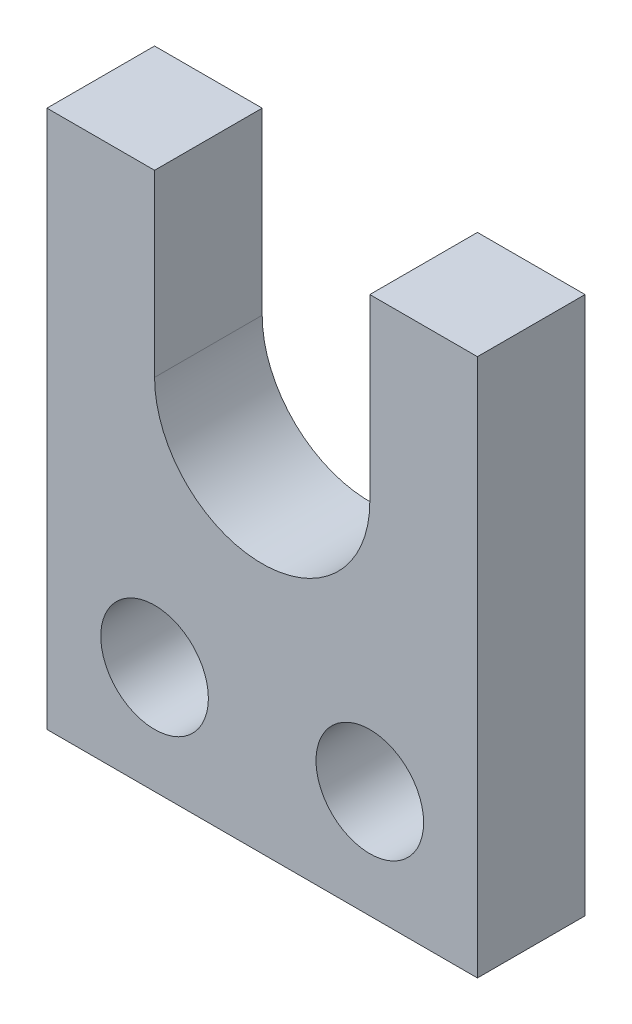
SolidWorks part; units mm, degrees
ref_plane "Front Plane" through (0, 0, 0) normal (0, 0, 1) x (1, 0, 0)
ref_plane "Top Plane" through (0, 0, 0) normal (0, 1, 0) x (1, 0, 0)
ref_plane "Right Plane" through (0, 0, 0) normal (1, 0, 0) x (0, 0, -1)
sketch "Sketch1" plane through (0, 0, 0) normal (0, 0, 1) x (1, 0, 0)
  line L1 (-6, 7.5) -> (6, 7.5)
  line L2 (-6, 7.5) -> (-6, -7.5)
  line L3 (-6, -7.5) -> (6, -7.5)
  line L4 (6, 7.5) -> (6, -7.5)
  line L5 (-6, 7.5) -> (6, -7.5) construction
  line L6 (-6, -7.5) -> (6, 7.5) construction
  circle A0 centre (-3, -4.5) radius 1.5
  circle A1 centre (3, -4.5) radius 1.5
  circle A2 centre (0, 16.5) radius 3 construction
  point P0 (0, 0)
  dimension "D3" = 3
  dimension "D4" = 3
  dimension "D5" = 6
  dimension "D1" = 12
  dimension "D2" = 15
  dimension "D6" = 21
  dimension "D7" = 0
  dimension "D8" = 3
  dimension "D9" = 3
  dimension "D10" = 6
  dimension "D11" = 0
extrude "Boss-Extrude1" add sketch "Sketch1" along normal blind 3
sketch "Sketch2" plane through (0, 0, 3) normal (0, 0, 1) x (1, 0, 0)
  line L0 (6, 7.5) -> (-6, 7.5) construction
  line L1 (-3, 7.5) -> (3, 7.5)
  line L2 (-3, 7.5) -> (-3, 2.5)
  line L3 (-3, 2.5) -> (3, 2.5) construction
  line L4 (3, 7.5) -> (3, 2.5)
  line L5 (-6, -7.5) -> (6, -7.5) construction
  line L6 (6, -7.5) -> (6, 7.5) construction
  line L7 (-6, 7.5) -> (-6, -7.5) construction
  arc A0 (3, 2.5) -> (-3, 2.5) centre (0, 2.5) cw
  dimension "D1" = 7
  dimension "D2" = 3
  dimension "D3" = 3
extrude "Cut-Extrude1" cut sketch "Sketch2" against normal up to next
